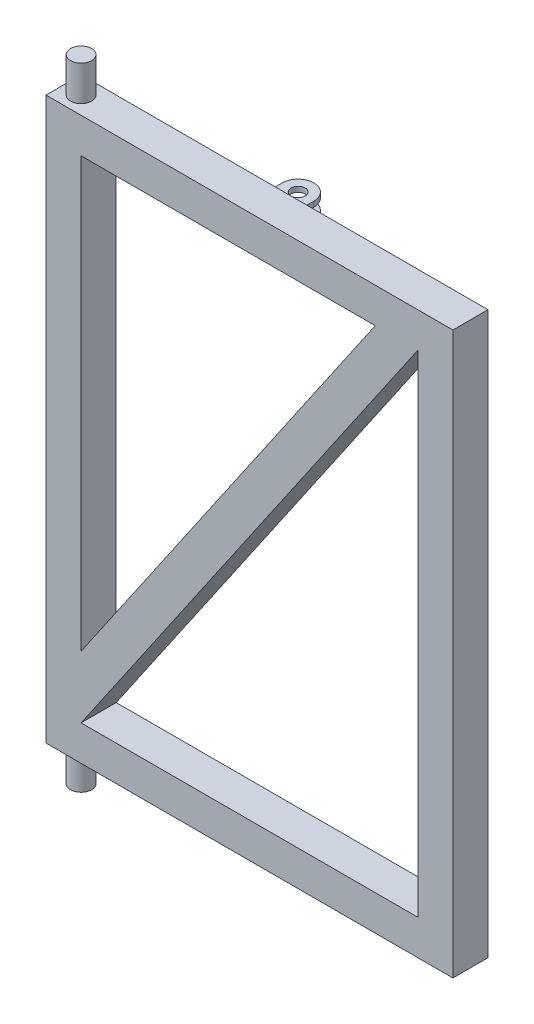
SolidWorks part; units mm, degrees
ref_plane "Plan de face" through (0, 0, 0) normal (0, 0, 1) x (1, 0, 0)
ref_plane "Plan de dessus" through (0, 0, 0) normal (0, 1, 0) x (1, 0, 0)
ref_plane "Plan de droite" through (0, 0, 0) normal (1, 0, 0) x (0, 0, -1)
sketch "Esquisse1" plane through (0, 0, 0) normal (0, 0, 1) x (1, 0, 0)
  line L1 (0, 0) -> (580, 0)
  line L2 (0, 0) -> (0, -800)
  line L3 (0, -800) -> (580, -800)
  line L4 (580, 0) -> (580, -800)
  line L8 (50, -50) -> (469.374, -50)
  line L9 (530, -50) -> (530, -750)
  line L10 (50, -750) -> (530, -750)
  line L11 (50, -50) -> (50, -661.5871)
  line L12 (530, -50) -> (50, -750)
  line L13 (469.374, -50) -> (50, -661.5871)
  line L15 (50, -50) -> (530, -50) construction
  line L16 (488.7636, -21.7236) -> (8.7636, -721.7236) construction
  line L17 (50, -50) -> (50, -750) construction
  dimension "D1" = 580
  dimension "D2" = 800
  dimension "D3" = 0
  dimension "D4" = 0
  dimension "D6" = 50
  dimension "D7" = 50
extrude "Boss.-Extru.1" add sketch "Esquisse1" along normal blind 50
sketch "Esquisse2" plane through (0, 0, 0) normal (0, 1, 0) x (1, 0, 0)
  line L0 (580, 0) -> (0, 0) construction
  line L1 (0, -50) -> (0, 0) construction
  circle A0 centre (25, -25) radius 15
  dimension "D1" = 25
  dimension "D2" = 30
  dimension "D3" = 25
extrude "Boss.-Extru.2" add sketch "Esquisse2" along normal blind 50
sketch "Esquisse3" plane through (0, -800, 0) normal (0, -1, 0) x (1, 0, 0)
  line L0 (0, 50) -> (580, 50) construction
  line L1 (0, 50) -> (0, 0) construction
  circle A0 centre (25, 25) radius 15.1806
  dimension "D1" = 25
  dimension "D2" = 25
extrude "Boss.-Extru.3" add sketch "Esquisse3" along normal blind 50
ref_plane "Plan1" through (0, -25, 0) normal (0, 1, 0) x (1, 0, 0)
sketch "Esquisse4" plane through (0, -25, 0) normal (0, 1, 0) x (1, 0, 0)
  line L0 (580, 0) -> (0, 0) construction
  line L1 (311.8283, -8.6781) -> (266.8283, -8.6781)
  line L2 (311.8283, -8.6781) -> (311.8283, 20)
  line L4 (266.8283, -8.6781) -> (266.8283, 20)
  arc A0 (311.8283, 20) -> (266.8283, 20) centre (289.3283, 20) ccw
  circle A1 centre (25, -25) radius 15 construction
  circle A2 centre (289.3283, 20) radius 10
  dimension "D3" = 264.3283
  dimension "D4" = 22.5
  dimension "D5" = 20
  dimension "D1" = 45
  dimension "D2" = 20
extrude "Boss.-Extru.4" add sketch "Esquisse4" along normal mid plane 30
sketch "Esquisse5" plane through (0, -25, 0) normal (0, 1, 0) x (1, 0, 0)
  line L1 (250.3427, 49.2248) -> (327.0135, 49.2248)
  line L2 (250.3427, 49.2248) -> (250.3427, 4.9408)
  line L3 (250.3427, 4.9408) -> (327.0135, 4.9408)
  line L4 (327.0135, 49.2248) -> (327.0135, 4.9408)
extrude "Enlèv. mat.-Extru.1" cut sketch "Esquisse5" against normal mid plane 15
